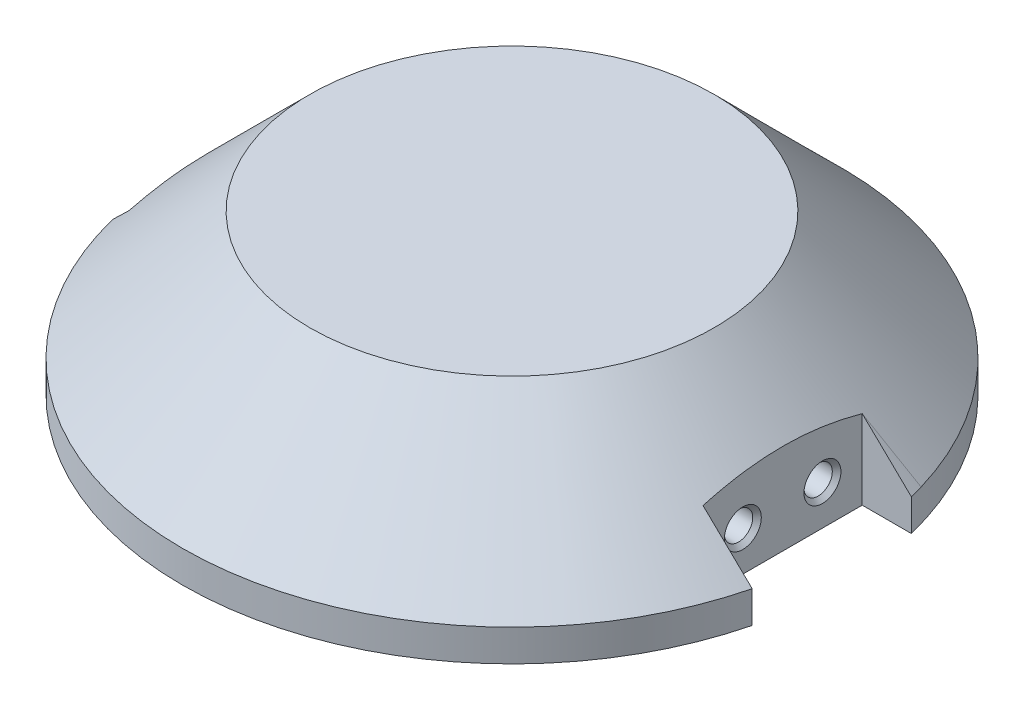
SolidWorks part; units mm, degrees
material "Chrome Stainless Steel"
ref_plane "Front Plane" through (0, 0, 0) normal (0, 0, 1) x (1, 0, 0)
ref_plane "Top Plane" through (0, 0, 0) normal (0, 1, 0) x (1, 0, 0)
ref_plane "Right Plane" through (0, 0, 0) normal (1, 0, 0) x (0, 0, -1)
ref_plane "Plane1" through (0, 0, 0) normal (0, 0, 1) x (1, 0, 0)
sketch "Sketch3" plane through (0, 0, 0) normal (0, 0, 1) x (1, 0, 0)
  line L0 (0, 0) -> (28.829, 0)
  line L1 (28.829, 0) -> (16.129, 12.7)
  line L2 (16.129, 12.7) -> (0, 12.7)
  line L3 (0, 12.7) -> (0, 0)
  dimension "D1" = 45
  dimension "D2" = 28.829
  dimension "D3" = 12.7
revolve "Revolve2" add sketch "Sketch3" angle 360 about L3
sketch "Sketch4" plane through (0, 0, 0) normal (0, 0, 1) x (1, 0, 0)
  line L0 (26.289, 0) -> (26.289, 2.54)
  line L1 (-28.829, 0) -> (28.829, 0) construction
  line L2 (28.829, 0) -> (16.129, 12.7) construction
  line L3 (26.289, 2.54) -> (32.1144, 2.54)
  line L4 (32.1144, 2.54) -> (32.1144, -2.2488)
  line L5 (32.1144, -2.2488) -> (26.289, -2.2488)
  line L6 (26.289, -2.2488) -> (26.289, 0)
  dimension "D1" = 2.54
ref_axis "Axis1" through (0, 0, 0) along (0, 1, 0)
revolve "Cut-Revolve1" cut sketch "Sketch4" angle 360 about axis through (0, 0, 0) along (0, 1, 0)
sketch "Sketch5" plane through (0, 0, 0) normal (0, -1, 0) x (1, 0, 0)
  line L0 (0, 0) -> (-26.289, 0) construction
  line L1 (6.985, 0) -> (-6.985, 0) construction
  line L2 (-26.289, -6.35) -> (-26.289, 6.35)
  line L3 (-26.289, 6.35) -> (-24.2062, 6.35)
  line L4 (-24.2062, 6.35) -> (-24.2062, -6.35)
  line L5 (-26.289, -6.35) -> (-24.2062, -6.35)
  circle A0 centre (0, 0) radius 26.289 construction
  point P11 (-24.2062, 0)
  dimension "D1" = 2.0828
  dimension "D2" = 12.7
extrude "Cut-Extrude1" cut sketch "Sketch5" against normal through all
sketch "Sketch8" plane through (-24.2062, 0, 0) normal (-1, 0, 0) x (0, 0, 1)
  circle A0 centre (3.175, 1.8034) radius 1.4605
  circle A1 centre (-3.175, 1.8034) radius 1.4605
hole_wizard "#4-40 Tapped Hole1" positions "Sketch10" profile "Sketch9" tap size "#4-40" standard "ANSI Inch"
sketch "Sketch10" plane through (-24.2062, 0, 0) normal (-1, 0, 0) x (0, 0, 1)
  point P0 (-3.175, 1.8034)
  point P3 (3.175, 1.8034)
sketch "Sketch9" plane through (-24.2062, 1.8034, -3.175) normal (0, 1, 0) x (0, 0, 1)
  line L0 (0, 0) -> (0, 8.2738)
  line L1 (0, 8.2738) -> (1.1303, 7.5946)
  line L2 (1.1303, 7.5946) -> (1.1303, 0.3429)
  line L3 (1.1303, 0.3429) -> (1.4732, 0)
  line L5 (1.4732, 0) -> (0, 0)
  line L6 (-1.1303, 0.3429) -> (-1.4732, 0) construction
  line L10 (0, 8.2738) -> (-1.1303, 7.5946) construction
  line L11 (0, -6.35) -> (0, 107.95) construction
  dimension "Tap Drill Dia." = 2.2606
  dimension "Tap Drill Depth" = 7.5946
  dimension "Near C'Sink Dia." = 2.9464
  dimension "Near C'Sink Angle" = 90
  dimension "Drill Angle" = 118
cosmetic thread "Hole Thread1" parameters "D1"=5.6896, "D2"=2.8448
cosmetic thread "Hole Thread2" parameters "D1"=5.6896, "D2"=2.8448
sketch "Sketch11" plane through (0, 0, 0) normal (0, 0, 1) x (1, 0, 0)
  line L0 (16.129, 12.7) -> (26.289, 2.54)
  line L1 (26.289, 0) -> (26.289, 2.54) construction
  line L2 (-25.5106, 2.54) -> (26.289, 2.54) construction
  line L3 (21.59, 7.239) -> (21.59, 0)
  line L4 (-25.5106, 0) -> (26.289, 0) construction
  dimension "D1" = 7.239
ref_plane "Plane2" through (21.59, 0, 0) normal (-1, 0, 0) x (0, 0, 1)
sketch "Sketch13" plane through (21.59, 0, 0) normal (-1, 0, 0) x (0, 0, 1)
  line L0 (0, 11.3319) -> (0, -4.8713) construction
  line L1 (0, 12.7) -> (0, 2.54) construction
  line L2 (6.35, 0) -> (-6.35, 0)
  line L3 (-26.289, 0) -> (26.289, 0) construction
  line L4 (-6.35, 0) -> (-6.35, 10.16)
  line L5 (-6.35, 10.16) -> (6.35, 10.16)
  line L6 (6.35, 0) -> (6.35, 10.16)
  point P12 (0, 10.16)
  point P13 (0, 0)
  dimension "D1" = 12.7
  dimension "D2" = 10.16
extrude "Cut-Extrude3" cut sketch "Sketch13" against normal through all
sketch "Sketch15" plane through (21.59, 0, 0) normal (1, 0, 0) x (0, 0, -1)
  line L0 (-6.35, 3.175) -> (6.35, 3.175) construction
  line L1 (-6.35, 0) -> (-6.35, 6.3245) construction
  line L2 (6.35, 6.3245) -> (6.35, 0) construction
  line L3 (6.35, 0) -> (-6.35, 0) construction
  line L4 (0, 0) -> (0, 3.175) construction
  line L5 (0, 3.175) -> (-6.35, 3.175) construction
  circle A0 centre (-3.175, 3.175) radius 3.175
  circle A1 centre (3.175, 3.175) radius 3.175
  point P11 (-3.175, 3.175)
  dimension "D1" = 3.175
hole_wizard "#4-40 Tapped Hole2" positions "Sketch17" profile "Sketch16" tap size "#4-40" standard "ANSI Inch"
sketch "Sketch17" plane through (21.59, 0, 0) normal (1, 0, 0) x (0, 0, -1)
  point P0 (-3.175, 3.175)
  point P3 (3.175, 3.175)
sketch "Sketch16" plane through (21.59, 3.175, 3.175) normal (0, 1, 0) x (0, 0, -1)
  line L0 (0, 0) -> (0, 8.2738)
  line L1 (0, 8.2738) -> (1.1303, 7.5946)
  line L2 (1.1303, 7.5946) -> (1.1303, 0.3429)
  line L3 (1.1303, 0.3429) -> (1.4732, 0)
  line L5 (1.4732, 0) -> (0, 0)
  line L6 (-1.1303, 0.3429) -> (-1.4732, 0) construction
  line L10 (0, 8.2738) -> (-1.1303, 7.5946) construction
  line L11 (0, -6.35) -> (0, 107.95) construction
  dimension "Tap Drill Dia." = 2.2606
  dimension "Tap Drill Depth" = 7.5946
  dimension "Near C'Sink Dia." = 2.9464
  dimension "Near C'Sink Angle" = 90
  dimension "Drill Angle" = 118
cosmetic thread "Hole Thread3" parameters "D1"=5.6896, "D2"=2.8448
cosmetic thread "Hole Thread4" parameters "D1"=5.6896, "D2"=2.8448
